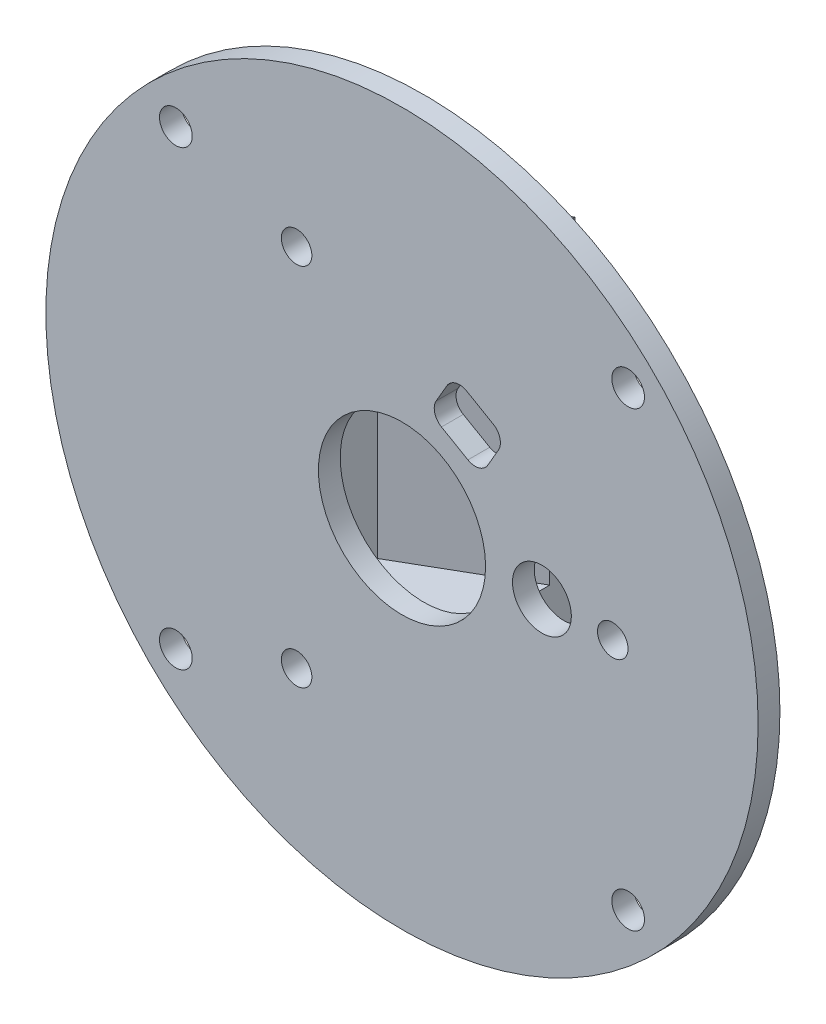
SolidWorks part; units mm, degrees
ref_plane "前视基准面" through (0, 0, 0) normal (0, 0, 1) x (1, 0, 0)
ref_plane "上视基准面" through (0, 0, 0) normal (0, 1, 0) x (1, 0, 0)
ref_plane "右视基准面" through (0, 0, 0) normal (1, 0, 0) x (0, 0, -1)
sketch "草图1" plane through (0, 0, 0) normal (0, 0, 1) x (1, 0, 0)
  line L10 (0, 0) -> (29, 0)
  line L11 (0, 0) -> (-14.5, 25.1147)
  line L12 (0, 0) -> (-14.5, -25.1147)
  circle A2 centre (0, 44) radius 1.6
  circle A4 centre (0, 0) radius 49
  circle A5 centre (44, 0) radius 1.6
  circle A7 centre (0, -44) radius 1.6
  circle A9 centre (-44, 0) radius 1.6
  circle A10 centre (29, 0) radius 2.1
  circle A11 centre (-14.5, 25.1147) radius 2.1
  circle A12 centre (-14.5, -25.1147) radius 2.1
  point P34 (0, 0)
  dimension "D1" = 4
sketch "草图2" plane through (0, 0, 0) normal (0, 0, 1) x (1, 0, 0)
  circle A0 centre (0, 0) radius 11.5
sketch "草图3" plane through (0, 0, 0) normal (0, 0, 1) x (1, 0, 0)
  circle A0 centre (0, 0) radius 8.6
sketch "草图5" plane through (0, 0, 0) normal (1, 0, 0) x (0, 0, -1)
  circle A0 centre (-59.5, 0) radius 1.5
sketch "草图6" plane through (0, 0, 0) normal (0, 0, 1) x (1, 0, 0)
  circle A0 centre (19.25, 0) radius 4.05
sketch "草图7" plane through (0, 0, 0) normal (0, 0, 1) x (1, 0, 0)
  line L3 (10.8022, 10.5058) -> (14.2725, 16.5146)
  line L8 (3.7014, 14.6068) -> (10.8022, 10.5058)
  line L9 (3.7014, 14.6068) -> (7.1717, 20.6156)
  line L10 (7.1717, 20.6156) -> (14.2725, 16.5146)
  dimension "D1" = 14.5
extrude "凸台-拉伸4" add sketch "草图1" along normal blind 13 contours A2 | A7 | A5 | A9 | A12 | A10 | A11
sketch "草图8" plane through (0, 0, 0) normal (0, 0, 1) x (1, 0, 0)
  circle A0 centre (0, 0) radius 49
extrude "凸台-拉伸5" add sketch "草图8" along normal blind 3
sketch "草图9" plane through (0, 0, 0) normal (0, 0, 1) x (1, 0, 0)
  circle A0 centre (0, 44) radius 2.1
  circle A1 centre (44, 0) radius 2.1
  circle A2 centre (0, -44) radius 2.1
  circle A3 centre (-44, 0) radius 2.1
  circle A4 centre (-14.5, 25.1147) radius 2.1
  circle A5 centre (-14.5, -25.1147) radius 2.1
  circle A6 centre (29, 0) radius 2.1
  point P12 (0, 0)
  dimension "D2" = 4.2
  dimension "D1" = 4
extrude "切除-拉伸2" cut sketch "草图9" along normal blind 13
extrude "切除-拉伸3" cut sketch "草图3" along normal blind 13 contours A0
extrude "切除-拉伸4" cut sketch "草图6" along normal blind 13 contours A0
extrude "切除-拉伸5" cut sketch "草图7" along normal blind 13 contours L10 L3 L8 L9
extrude "切除-拉伸6" cut sketch "草图2" along normal blind 13 contours A0
fillet "圆角1" radius 2 4 edges at (7.1717, 20.6156, 1.5) (14.2725, 16.5146, 1.5) (10.8022, 10.5058, 1.5) (3.7014, 14.6068, 1.5)
sketch "草图10" plane through (0, 0, 3) normal (0, 0, 1) x (1, 0, 0)
  line L0 (-31.1127, 31.1127) -> (31.1127, -31.1127) construction
  line L1 (-31.1127, -31.1127) -> (31.1127, 31.1127) construction
  line L2 (-44, 0) -> (44, 0) construction
  circle A0 centre (0, 0) radius 44 construction
  circle A1 centre (-31.1127, 31.1127) radius 2.25
  circle A2 centre (31.1127, 31.1127) radius 2.25
  circle A3 centre (31.1127, -31.1127) radius 2.25
  circle A4 centre (-31.1127, -31.1127) radius 2.25
  dimension "D3" = 4.5
  dimension "D1" = 45
  dimension "D2" = 45
extrude "切除-拉伸7" cut sketch "草图10" against normal up to next
sketch "草图11" plane through (0, 0, 3) normal (0, 0, 1) x (1, 0, 0)
  circle A0 centre (-44, 0) radius 2.1
  circle A1 centre (0, -44) radius 2.1
  circle A2 centre (44, 0) radius 2.1
  circle A3 centre (0, 44) radius 2.1
extrude "凸台-拉伸6" add sketch "草图11" against normal up to surface (3 mm away) up to face at (-28.8627, -31.1127, 0)
sketch "草图12" plane through (0, 0, 0) normal (0, 0, -1) x (-1, 0, 0)
  line L0 (36, -24) -> (36, 24) construction
  line L1 (36, -24) -> (36, 24)
  line L2 (0, 0) -> (36, 0) construction
  line L3 (36, -24) -> (26, -24)
  line L4 (36, -24) -> (36, 24)
  line L5 (36, 24) -> (26, 24)
  line L6 (26, -24) -> (26, 24)
  line L7 (36, 0) -> (49, 0) construction
  circle A0 centre (0, 0) radius 49 construction
  point P7 (36, 0)
  dimension "D1" = 10
  dimension "D2" = 48
  dimension "D3" = 26
extrude "凸台-拉伸7" add sketch "草图12" along normal blind 10 contours L6 L3 L1 L5
sketch "草图13" plane through (0, 24, 0) normal (0, 1, 0) x (1, 0, 0)
  line L0 (-36, 0) -> (0, 20.7846)
  line L1 (0, 0) -> (-36, 0)
  line L2 (0, 20.7846) -> (0, 0)
  line L3 (-30, 0) -> (0, 17.3205)
  line M4 (-36, 0) -> (-26, 0)
  line M5 (-26, 0) -> (-26, 10)
  dimension "D1" = 30
  dimension "D2" = 3
extrude "凸台-拉伸8" add sketch "草图13" against normal blind 48 contours L3 L2 L0 M5 | L3 L0 M4 M5
sketch "草图16" plane through (0, 0, 0) normal (0, 0, -1) x (-1, 0, 0)
  line L0 (36, -24) -> (36, 24) construction
  line L5 (0, -24) -> (0, 24) construction
  line L6 (0, 22.1147) -> (36, 22.1147)
  line L7 (0, 22.1147) -> (0, 18.1147)
  line L8 (0, 18.1147) -> (36, 18.1147)
  line L9 (36, 22.1147) -> (36, 18.1147)
  line L10 (36, 0) -> (0, 0) construction
  line L11 (0, -18.1147) -> (36, -18.1147)
  line L12 (36, -22.1147) -> (36, -18.1147)
  line L13 (0, -22.1147) -> (36, -22.1147)
  line L14 (0, -22.1147) -> (0, -18.1147)
  line L16 (15, 22.1147) -> (27, 22.1147)
  line L17 (15, 22.1147) -> (15, -22.1147)
  line L18 (15, -22.1147) -> (27, -22.1147)
  line L19 (27, 22.1147) -> (27, -22.1147)
  circle A0 centre (14.5, 25.1147) radius 2.1 construction
  circle A1 centre (0, 0) radius 11.5 construction
  line M11 (26, -24) -> (26, 24)
  dimension "D1" = 3
  dimension "D2" = 4
  dimension "D3" = 15
  dimension "D4" = 12
extrude "凸台-拉伸9" add sketch "草图16" along normal blind 18 contours L17 L11 L14 L13 | L11 L17 L13 M11 | L10 L17 L11 M11 | L17 L6 L7 L8 | L6 L17 L8 M11 | L10 L8 L17 M11
sketch "草图14" plane through (0, 24, 0) normal (0, 1, 0) x (1, 0, 0)
  line L5 (0, 20.7846) -> (-36, 20.7846)
  line L7 (-36, 20.7846) -> (-36, 0)
  line L8 (-36, 0) -> (0, 20.7846)
extrude "切除-拉伸8" cut sketch "草图14" against normal blind 48
